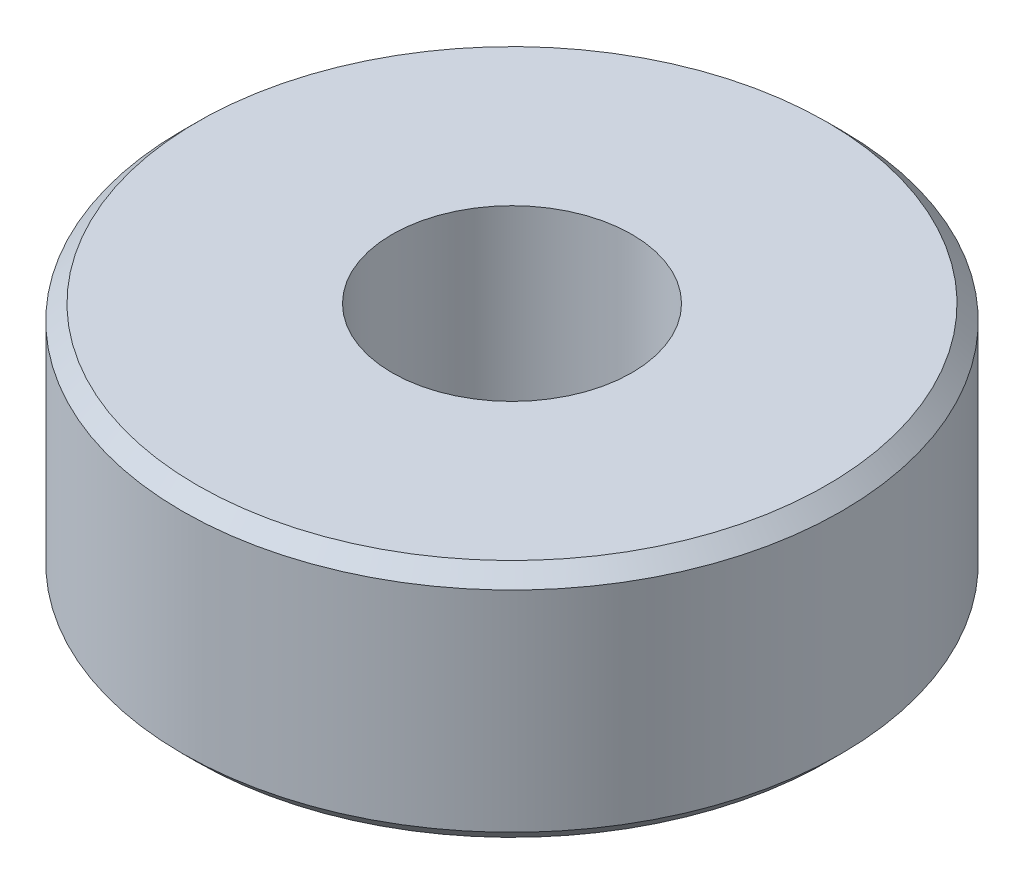
SolidWorks part; units mm, degrees
ref_plane "Front Plane" through (0, 0, 0) normal (0, 0, 1) x (1, 0, 0)
ref_plane "Top Plane" through (0, 0, 0) normal (0, 1, 0) x (1, 0, 0)
ref_plane "Right Plane" through (0, 0, 0) normal (1, 0, 0) x (0, 0, -1)
sketch "Sketch1" plane through (0, 0, 0) normal (0, 1, 0) x (1, 0, 0)
  circle A0 centre (0, 0) radius 11
  circle A1 centre (0, 0) radius 4
  dimension "D1" = 22
  dimension "D2" = 8
extrude "Boss-Extrude1" add sketch "Sketch1" along normal blind 8
chamfer "Chamfer1" distance 0.5 angle 45 3 edges at (0, 8, 11) (0, 0, 4) (0, 0, 11)
